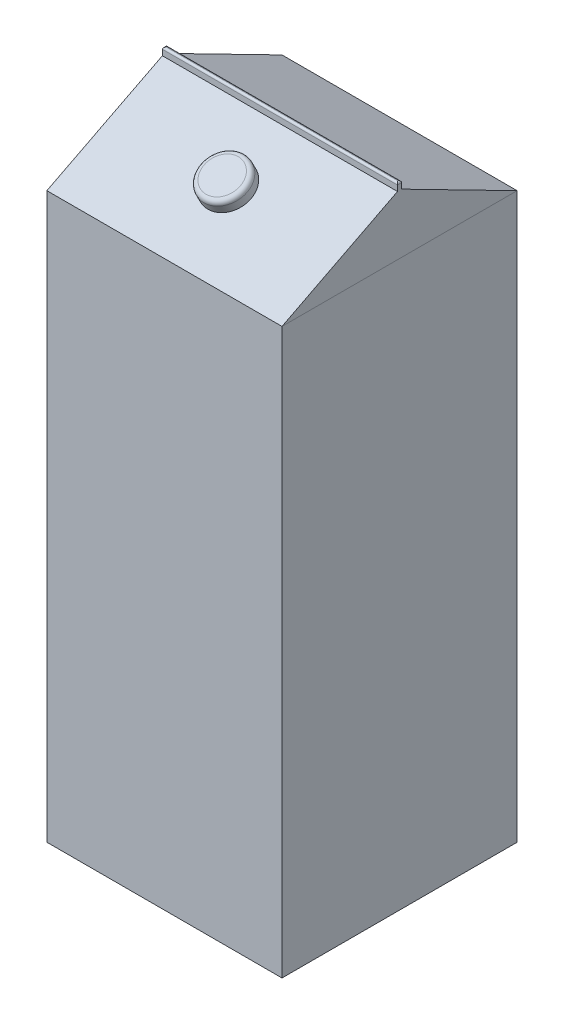
SolidWorks part; units mm, degrees
ref_plane "Front Plane" through (0, 0, 0) normal (0, 0, 1) x (1, 0, 0)
ref_plane "Top Plane" through (0, 0, 0) normal (0, 1, 0) x (1, 0, 0)
ref_plane "Right Plane" through (0, 0, 0) normal (1, 0, 0) x (0, 0, -1)
sketch "Sketch3" plane through (0, 0, 0) normal (1, 0, 0) x (0, 0, -1)
  line L1 (0, 0) -> (63.5, 0)
  line L2 (0, 0) -> (0, 152.4)
  line L3 (0, 152.4) -> (63.5, 152.4)
  line L4 (63.5, 0) -> (63.5, 152.4)
  dimension "D1" = 152.4
  dimension "D2" = 63.5
extrude "Boss-Extrude3" add sketch "Sketch3" along normal blind 63.5
sketch "Sketch5" plane through (0, 0, 0) normal (-1, 0, 0) x (0, 0, 1)
  line L0 (-63.5, 152.4) -> (-31.75, 168.6403)
  line L1 (-31.75, 168.6403) -> (0, 152.4)
  line L2 (-32.3062, 168.3557) -> (-32.3062, 170.3804)
  line L3 (-32.3062, 170.3804) -> (-31.1948, 170.3804)
  line L4 (-31.1948, 170.3804) -> (-31.1948, 168.3563)
  line L5 (-63.5, 152.4) -> (0, 152.4)
  line M2 (0, 152.4) -> (-63.5, 152.4)
extrude "Boss-Extrude5" add sketch "Sketch5" against normal blind 63.5 separate body contours L1 L0 M2 | L4 L3 L2 L0 L1
fillet "Fillet5" radius 0.508 4 edges at (31.75, 170.3804, -32.3062) (63.5, 170.3804, -31.7505) (31.75, 170.3804, -31.1948) (0, 170.3804, -31.7505)
sketch "Sketch6" plane through (0, 120.7955, 61.7874) normal (0, 0.8903, 0.4554) x (1, 0, 0)
  circle A0 centre (31.9758, 88.4849) radius 6.1648
extrude "Boss-Extrude6" add sketch "Sketch6" along normal blind 3.556
fillet "Fillet6" radius 1.27 1 edges at (31.9758, 161.449, -9.8822)
